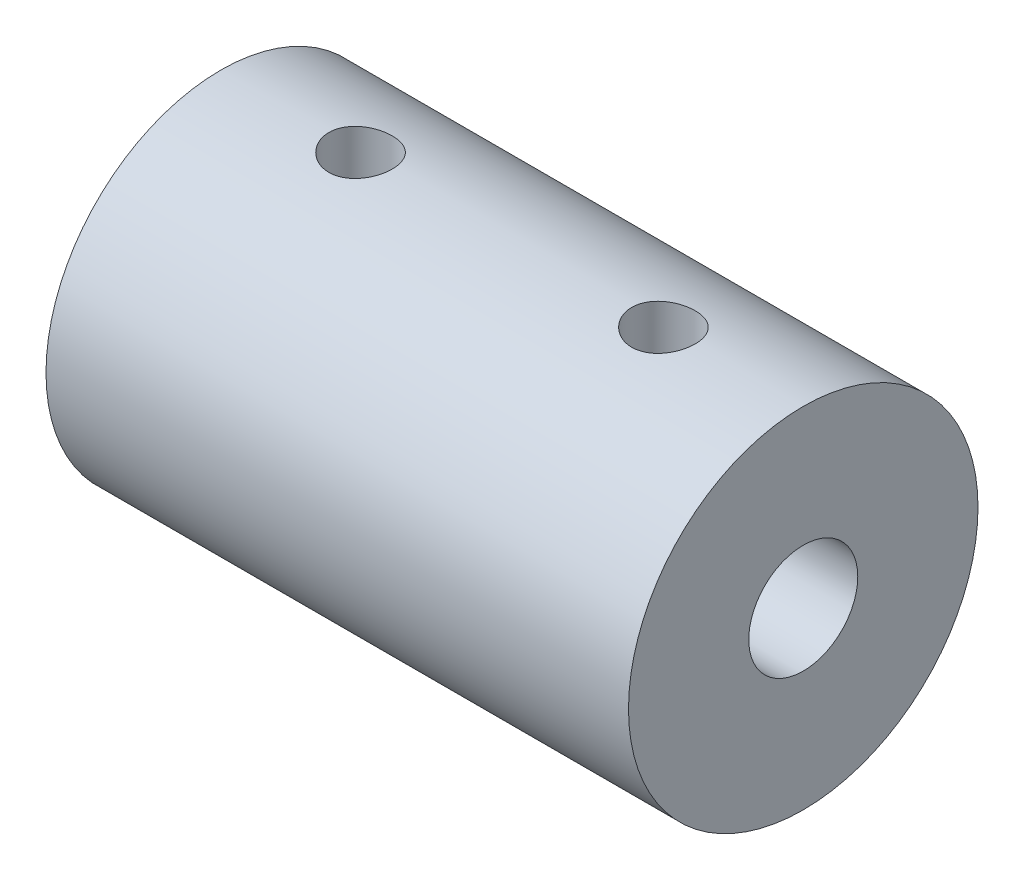
SolidWorks part; units mm, degrees
ref_plane "Front Plane" through (0, 0, 0) normal (0, 0, 1) x (1, 0, 0)
ref_plane "Top Plane" through (0, 0, 0) normal (0, 1, 0) x (1, 0, 0)
ref_plane "Right Plane" through (0, 0, 0) normal (1, 0, 0) x (0, 0, -1)
sketch "Sketch1" plane through (0, 0, 0) normal (1, 0, 0) x (0, 0, -1)
  circle A0 centre (0, 0) radius 9.525
  dimension "D1" = 19.05
extrude "Boss-Extrude1" add sketch "Sketch1" along normal mid plane 31.75
hole_wizard "A Diameter Drive Shaft Side" positions "Sketch2" profile "Sketch4" hole size "A" standard "ANSI Inch"
sketch "Sketch2" plane through (-15.875, 0, 0) normal (-1, 0, 0) x (0, 0, 1)
  point P0 (0, 0)
sketch "Sketch4" plane through (-15.875, 0, 0) normal (0, 1, 0) x (0, 0, 1)
  line L0 (0, 0) -> (0, 14.4856)
  line L1 (0, 14.4856) -> (2.9718, 12.7)
  line L2 (2.9718, 12.7) -> (2.9718, 0)
  line L5 (2.9718, 0) -> (0, 0)
  line L10 (0, 14.4856) -> (-2.9718, 12.7) construction
  line L11 (0, -6.35) -> (0, 107.95) construction
  dimension "Hole Dia." = 5.9436
  dimension "Hole Depth" = 12.7
  dimension "Drill Angle" = 118
hole_wizard "A Diameter Motor Shaft Side" positions "Sketch5" profile "Sketch6" hole size "A" standard "ANSI Inch"
sketch "Sketch5" plane through (15.875, 0, 0) normal (1, 0, 0) x (0, 0, -1)
  point P0 (0, 0)
sketch "Sketch6" plane through (15.875, 0, 0) normal (0, 1, 0) x (0, 0, -1)
  line L0 (0, 0) -> (0, 14.4856)
  line L1 (0, 14.4856) -> (2.9718, 12.7)
  line L2 (2.9718, 12.7) -> (2.9718, 0)
  line L5 (2.9718, 0) -> (0, 0)
  line L10 (0, 14.4856) -> (-2.9718, 12.7) construction
  line L11 (0, -6.35) -> (0, 107.95) construction
  dimension "Hole Dia." = 5.9436
  dimension "Hole Depth" = 12.7
  dimension "Drill Angle" = 118
ref_plane "Plane1" through (0, 9.525, 0) normal (0, 1, 0) x (1, 0, 0)
hole_wizard "#8-32 Tapped Hole1" positions "Sketch7" profile "Sketch8" tap size "#8-32" standard "ANSI Inch"
sketch "Sketch7" plane through (0, 9.525, 0) normal (0, 1, 0) x (1, 0, 0)
  line L0 (-8.255, 0) -> (8.255, 0) construction
  line L2 (-15.875, 9.525) -> (-15.875, -9.525) construction
  point P0 (-8.255, 0)
  point P2 (8.255, 0)
  point P11 (0, 0)
  dimension "D1" = 7.62
sketch "Sketch8" plane through (-8.255, 9.525, 0) normal (1, 0, 0) x (0, 0, 1)
  line L0 (0, 0) -> (0, 6.5532)
  line L1 (0, 6.5532) -> (1.7272, 6.5532)
  line L2 (1.7272, 6.5532) -> (1.7272, 0)
  line L5 (1.7272, 0) -> (0, 0)
  line L11 (0, -6.35) -> (0, 107.95) construction
  dimension "Thru Tap Drill Dia." = 3.4544
  dimension "Thru Tap Drill Depth" = 6.5532
cosmetic thread "Hole Thread1"
cosmetic thread "Hole Thread2"
